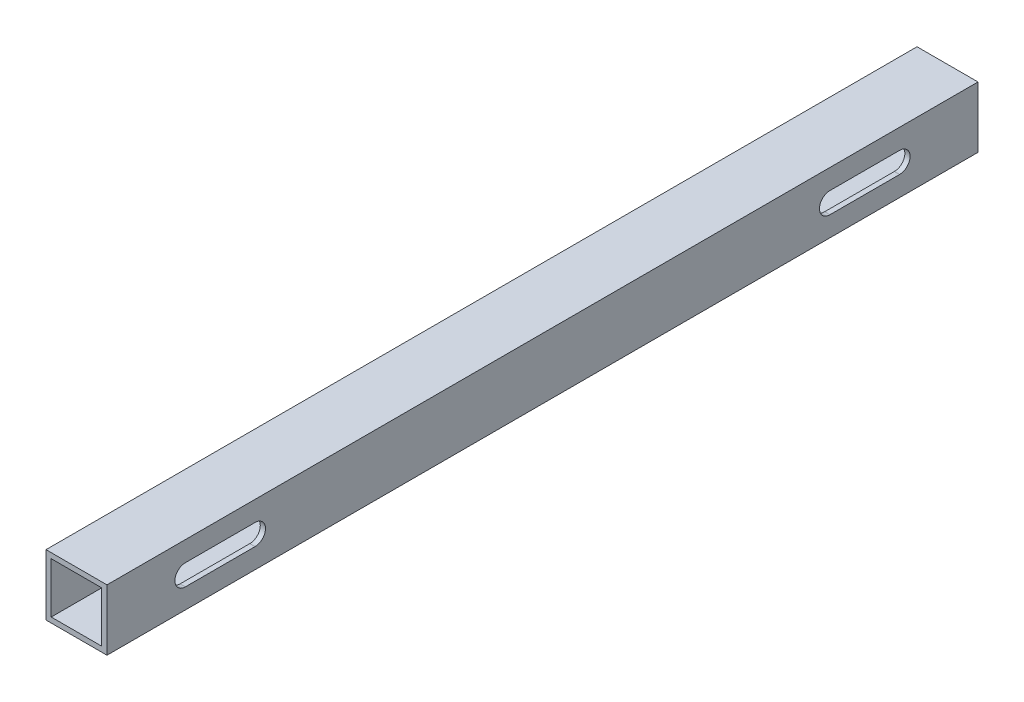
SolidWorks part; units mm, degrees
ref_plane "Płaszczyzna przednia" through (0, 0, 0) normal (0, 0, 1) x (1, 0, 0)
ref_plane "Płaszczyzna górna" through (0, 0, 0) normal (0, 1, 0) x (1, 0, 0)
ref_plane "Płaszczyzna prawa" through (0, 0, 0) normal (1, 0, 0) x (0, 0, -1)
sketch "Szkic1" plane through (0, 0, 0) normal (0, 0, 1) x (1, 0, 0)
  line L1 (-17.5, -17.5) -> (17.5, -17.5)
  line L2 (-17.5, -17.5) -> (-17.5, 17.5)
  line L3 (-17.5, 17.5) -> (17.5, 17.5)
  line L4 (17.5, -17.5) -> (17.5, 17.5)
  line L5 (-17.5, -17.5) -> (17.5, 17.5) construction
  line L6 (-17.5, 17.5) -> (17.5, -17.5) construction
  line L7 (-14.5, -14.5) -> (14.5, -14.5)
  line L8 (-14.5, -14.5) -> (-14.5, 14.5)
  line L9 (-14.5, 14.5) -> (14.5, 14.5)
  line L10 (14.5, -14.5) -> (14.5, 14.5)
  line L11 (-14.5, -14.5) -> (14.5, 14.5) construction
  line L12 (-14.5, 14.5) -> (14.5, -14.5) construction
  point P0 (0, 0)
  point P5 (0, 0)
  dimension "D1" = 35
  dimension "D2" = 29
extrude "Dodanie-wyciągnięcie1" add sketch "Szkic1" along normal blind 500
sketch "Szkic2" plane through (17.5, 0, 0) normal (1, 0, 0) x (0, 0, -1)
  line L0 (-455, 0) -> (-415, 0) construction
  line L1 (-455, 6) -> (-415, 6)
  line L2 (-455, -6) -> (-415, -6)
  line L3 (-45, 0) -> (-85, 0) construction
  line L4 (-45, -6) -> (-85, -6)
  line L5 (-45, 6) -> (-85, 6)
  line L7 (-250, 99.1275) -> (-250, -54.3417) construction
  line L8 (0, -17.5) -> (0, 17.5) construction
  line L9 (-500, -17.5) -> (-500, 17.5) construction
  arc A0 (-455, 6) -> (-455, -6) centre (-455, 0) ccw
  arc A1 (-415, -6) -> (-415, 6) centre (-415, 0) ccw
  arc A2 (-45, -6) -> (-45, 6) centre (-45, 0) ccw
  arc A3 (-85, 6) -> (-85, -6) centre (-85, 0) ccw
  point P3 (-435, 0)
  point P8 (-65, 0)
  dimension "D2" = 6
  dimension "D1" = 40
  dimension "D3" = 330
extrude "Wytnij-wyciągnięcie1" cut sketch "Szkic2" against normal up to surface (35 mm away) up to face at (-17.5, 0, 250)
